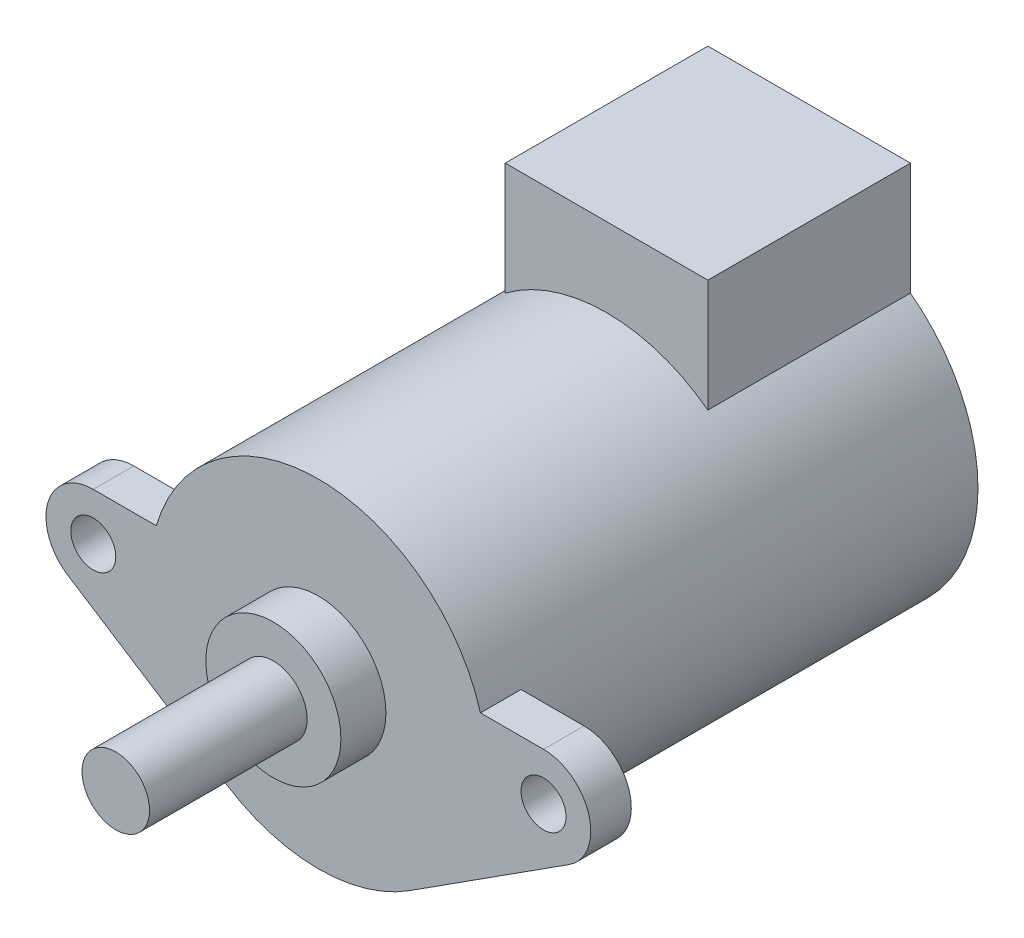
SolidWorks part; units mm, degrees
ref_plane "Piano frontale" through (0, 0, 0) normal (0, 0, 1) x (1, 0, 0)
ref_plane "Piano superiore" through (0, 0, 0) normal (0, 1, 0) x (1, 0, 0)
ref_plane "Piano destro" through (0, 0, 0) normal (1, 0, 0) x (0, 0, -1)
sketch "Schizzo1" plane through (0, 0, 0) normal (0, 1, 0) x (1, 0, 0)
  line L0 (7.5, 20) -> (0, 20)
  line L1 (0, 20) -> (0, -1.8)
  line L2 (0, -1.8) -> (7.5, -1.8)
  line L3 (7.5, -1.8) -> (7.5, 20)
  line L4 (0, 20) -> (0, -1.8) construction
revolve "Rivoluzione1" add sketch "Schizzo1" angle 360 about L4
ref_plane "Piano4" through (0, 0, 1.8) normal (0, 0, 1) x (1, 0, 0)
sketch "Schizzo2" plane through (0, 0, 1.8) normal (0, 0, 1) x (1, 0, 0)
  line L0 (-11.134, -1.7675) -> (-4.05, -6.3125)
  line L1 (-7.2, 2.1) -> (-10, 2.1)
  arc A0 (-10, 2.1) -> (-11.134, -1.7675) centre (-10, 0) ccw
  arc A1 (-4.05, -6.3125) -> (-7.2, 2.1) centre (0, 0) cw
extrude "Estrusione-Estrusione1" add sketch "Schizzo2" against normal blind 1.8
sketch "Schizzo3" plane through (0, 0, 1.8) normal (0, 0, 1) x (1, 0, 0)
  line L0 (10, 2.1) -> (7.2, 2.1)
  line L1 (4.05, -6.3125) -> (11.134, -1.7675)
  arc A0 (11.134, -1.7675) -> (10, 2.1) centre (10, 0) ccw
  arc A1 (7.2, 2.1) -> (4.05, -6.3125) centre (0, 0) cw
extrude "Estrusione-Estrusione2" add sketch "Schizzo3" against normal blind 1.8
sketch "Schizzo4" plane through (0, 0, 1.8) normal (0, 0, 1) x (1, 0, 0)
  circle A0 centre (0, 0) radius 3
extrude "Estrusione-Estrusione3" add sketch "Schizzo4" along normal blind 2
sketch "Schizzo5" plane through (0, 0, 3.8) normal (0, 0, 1) x (1, 0, 0)
  circle A0 centre (0, 0) radius 1.5
extrude "Estrusione-Estrusione4" add sketch "Schizzo5" along normal blind 7
ref_plane "Piano5" through (0, 11, 0) normal (0, 1, 0) x (-1, 0, 0)
sketch "Schizzo6" plane through (0, 11, 0) normal (0, 1, 0) x (-1, 0, 0)
  line L0 (-4.5, -11) -> (-4.5, -20)
  line L1 (-4.5, -20) -> (4.5, -20)
  line L2 (4.5, -20) -> (4.5, -11)
  line L3 (4.5, -11) -> (-4.5, -11)
extrude "Estrusione-Estrusione5" add sketch "Schizzo6" against normal up to next
sketch "Schizzo7" plane through (0, 0, -20) normal (0, 0, -1) x (-1, 0, 0)
  circle A0 centre (0, 0) radius 1
extrude "Estrusione-Estrusione6" add sketch "Schizzo7" along normal blind 1.5
hole_wizard "Foro1" positions "Schizzo9" profile "Schizzo8" legacy
sketch "Schizzo9" plane through (0, 0, 0) normal (0, 0, -1) x (-1, 0, 0)
  point P0 (-10, 0)
sketch "Schizzo8" plane through (10, 0, 0) normal (1, 0, 0) x (0, 1, 0)
  line L0 (0, 0) -> (0, 10.8)
  line L1 (0, 10.8) -> (1, 10.8)
  line L2 (1, 10.8) -> (1, 0)
  line L3 (1, 0) -> (0, 0)
  line L4 (0, 110) -> (0, -10) construction
  dimension "Diameter" = 2
  dimension "Depth" = 10.8
hole_wizard "Foro2" positions "Schizzo11" profile "Schizzo10" legacy
sketch "Schizzo11" plane through (0, 0, 0) normal (0, 0, -1) x (-1, 0, 0)
  point P0 (10, 0)
sketch "Schizzo10" plane through (-10, 0, 0) normal (1, 0, 0) x (0, 1, 0)
  line L0 (0, 0) -> (0, 10.8)
  line L1 (0, 10.8) -> (1, 10.8)
  line L2 (1, 10.8) -> (1, 0)
  line L3 (1, 0) -> (0, 0)
  line L4 (0, 110) -> (0, -10) construction
  dimension "Diameter" = 2
  dimension "Depth" = 10.8
